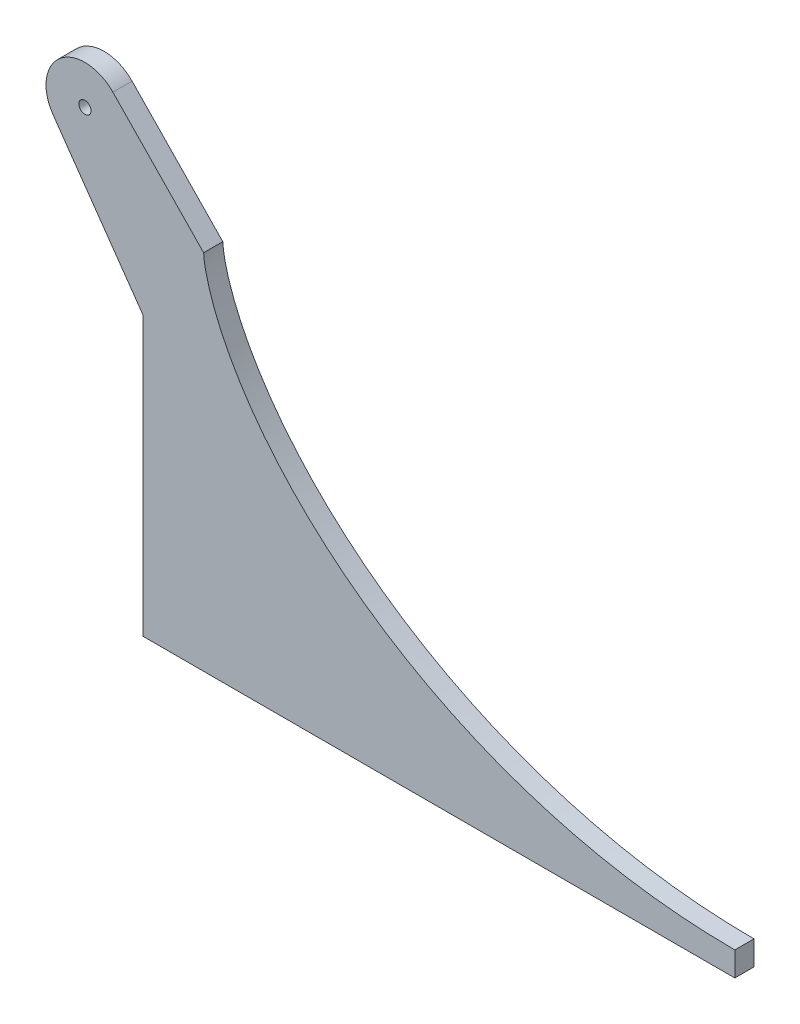
SolidWorks part; units mm, degrees
material "Oak"
ref_plane "Front Plane" through (0, 0, 0) normal (0, 0, 1) x (1, 0, 0)
ref_plane "Top Plane" through (0, 0, 0) normal (0, 1, 0) x (1, 0, 0)
ref_plane "Right Plane" through (0, 0, 0) normal (1, 0, 0) x (0, 0, -1)
sketch "Sketch1" plane through (0, 0, 0) normal (0, 0, 1) x (1, 0, 0)
  line L0 (-154.4814, -6.35) -> (-154.4814, 66.3474)
  line L1 (-177.8959, 99.7867) -> (-154.4814, 66.3474)
  line L2 (-154.4814, -6.35) -> (0, -6.35)
  line L3 (0, -6.35) -> (0, 0)
  line L4 (-169.5733, 105.6142) -> (-118.7733, 105.6142) construction
  line L5 (-169.5733, 105.6142) -> (-121.8369, 88.2396) construction
  line L6 (-121.8369, 88.2396) -> (-104.8412, 134.9349) construction
  line L7 (-138.0375, 84.2706) -> (-132.3265, 57.9556) construction
  line L9 (-162.2744, 112.6819) -> (-138.6064, 88.2396)
  circle A0 centre (-121.8369, 88.2396) radius 16.6687 construction
  circle A1 centre (-169.5733, 105.6142) radius 50.8 construction
  arc A3 (-177.8959, 99.7867) -> (-162.2744, 112.6819) centre (-169.5733, 105.6142) cw
  spline S0 degree 4 poles (-138.6064, 88.2396) (-138.6064, 88.2065) (-138.6049, 88.1343) (-138.5978, 87.982) (-138.5845, 87.768) (-138.5634, 87.5118) (-138.5143, 87.0234) (-138.4252, 86.3366) (-138.2627, 85.3402) (-137.9978, 84.039) (-137.5439, 82.1639) (-136.7091, 79.3328) (-135.3815, 75.6924) (-133.4271, 71.3116) (-130.9787, 66.686) (-128.2488, 62.2009) (-125.2784, 57.8718) (-121.923, 53.476) (-117.4999, 48.2548) (-111.8465, 42.3725) (-104.8067, 36.0327) (-96.4812, 29.6258) (-87.7118, 23.8431) (-78.5622, 18.6846) (-69.0882, 14.1503) (-59.3407, 10.2402) (-49.3653, 6.9542) (-41.1115, 4.7916) (-34.6941, 3.4205) (-30.1777, 2.5974) (-27.5868, 2.166) (-24.3494, 1.6756) (-20.4356, 1.165) (-15.8882, 0.6832) (-11.2784, 0.3379) (-7.392, 0.1395) (-4.3526, 0.0486) (-2.4771, 0.0124) (-0.6178, -0.0003) (0.366, -0.001) (1.7, 0.0063) (2.7346, 0.0201) (3.8728, 0.0408) (4.9554, 0.0684) (6.0693, 0.1028) (7.1654, 0.1442) (8.546, 0.2045) (10.1961, 0.2907) (12.1241, 0.4113) (14.0479, 0.5561) (15.697, 0.6974) (16.7946, 0.8008) (17.3438, 0.8548) (17.618, 0.8824) knots 0 0 0 0 0 0.000751 0.001501 0.003003 0.004504 0.006005 0.011633 0.01726 0.025308 0.033355 0.051378 0.078048 0.105081 0.132113 0.159146 0.186178 0.213211 0.246016 0.300081 0.354147 0.408212 0.462277 0.516343 0.570408 0.624473 0.678538 0.732604 0.74612 0.759636 0.773152 0.786669 0.813701 0.840734 0.867767 0.881283 0.894799 0.901946 0.909093 0.914775 0.920456 0.926138 0.93182 0.937501 0.943183 0.948865 0.954546 0.96591 0.977273 0.988637 0.994318 1 1 1 1 1 construction
  spline S1 degree 4 poles (-138.6064, 88.2396) (-138.6064, 88.2065) (-138.6049, 88.1343) (-138.5978, 87.982) (-138.5845, 87.768) (-138.5634, 87.5118) (-138.5143, 87.0234) (-138.4252, 86.3366) (-138.2627, 85.3402) (-137.9978, 84.039) (-137.5439, 82.1639) (-136.7091, 79.3328) (-135.3815, 75.6924) (-133.4271, 71.3116) (-130.9787, 66.686) (-128.2488, 62.2009) (-125.2784, 57.8718) (-121.923, 53.476) (-117.4999, 48.2548) (-111.8465, 42.3725) (-104.8067, 36.0327) (-96.4812, 29.6258) (-87.7118, 23.8431) (-78.5622, 18.6846) (-69.0882, 14.1503) (-59.3407, 10.2402) (-49.3653, 6.9542) (-41.1115, 4.7916) (-34.6941, 3.4205) (-30.1777, 2.5974) (-27.5868, 2.166) (-24.3494, 1.6756) (-20.4356, 1.165) (-15.8882, 0.6832) (-11.2784, 0.3379) (-7.392, 0.1395) (-4.3526, 0.0486) (-2.4771, 0.0124) (-0.9332, 0.0018) (-0.3153, 0) (0, 0) knots 0 0 0 0 0 0.000751 0.001501 0.003003 0.004504 0.006005 0.011633 0.01726 0.025308 0.033355 0.051378 0.078048 0.105081 0.132113 0.159146 0.186178 0.213211 0.246016 0.300081 0.354147 0.408212 0.462277 0.516343 0.570408 0.624473 0.678538 0.732604 0.74612 0.759636 0.773152 0.786669 0.813701 0.840734 0.867767 0.881283 0.894799 0.901946 0.909093 0.909093 0.909093 0.909093 0.909093
  point P6 (-154.4814, 57.9556)
  dimension "D4" = 33.3375
  dimension "D5" = 10.16
  dimension "D7" = 145
  dimension "D1" = 138.6064
  dimension "D2" = 6.35
  dimension "D3" = 15.875
  dimension "D6" = 20
  dimension "D9" = 50.8
extrude "Boss-Extrude1" add sketch "Sketch1" along normal mid plane 5
sketch "Sketch3" plane through (0, 0, 2.5) normal (0, 0, 1) x (1, 0, 0)
  circle A0 centre (-169.5733, 105.6142) radius 1.5875
  dimension "D1" = 3.175
extrude "Cut-Extrude1" cut sketch "Sketch3" against normal through all
